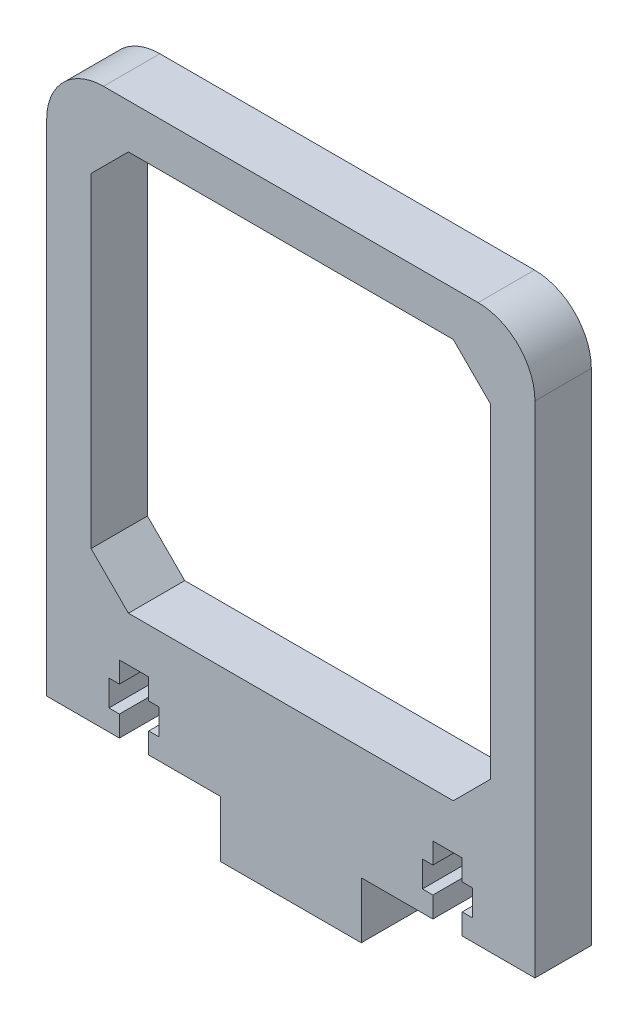
SolidWorks part; units mm, degrees
ref_plane "Front Plane" through (0, 0, 0) normal (0, 0, 1) x (1, 0, 0)
ref_plane "Top Plane" through (0, 0, 0) normal (0, 1, 0) x (1, 0, 0)
ref_plane "Right Plane" through (0, 0, 0) normal (1, 0, 0) x (0, 0, -1)
sketch "Sketch1" plane through (0, 0, 0) normal (0, 0, 1) x (1, 0, 0)
  line L0 (36.5923, 45) -> (-36.5923, 45)
  line L1 (-45, 36.5923) -> (-45, -36.5923)
  line L2 (-36.5923, -45) -> (36.5923, -45)
  line L3 (45, -36.5923) -> (45, 36.5923)
  arc A0 (45, 36.5923) -> (36.5923, 45) centre (0, 0) ccw
  arc A1 (-36.5923, 45) -> (-45, 36.5923) centre (0, 0) ccw
  arc A2 (-45, -36.5923) -> (-36.5923, -45) centre (0, 0) ccw
  arc A3 (36.5923, -45) -> (45, -36.5923) centre (0, 0) ccw
sketch "Sketch2" plane through (0, 0, 0) normal (0, 0, 1) x (1, 0, 0)
  line L0 (-55, 55) -> (-55, -70.38)
  line L1 (-55, -70.38) -> (55, -70.38)
  line L2 (55, -70.38) -> (55, 55)
  line L3 (55, 55) -> (-55, 55)
  line L4 (-45, 36.5923) -> (-45, -36.5923) construction
  line L5 (45, -36.5923) -> (45, 36.5923) construction
  line L6 (36.5923, 45) -> (-36.5923, 45) construction
  line L7 (-45, -36.5923) -> (-45, 36.5923)
  line L8 (-45, 36.5923) -> (-36.5923, 45)
  line L9 (-36.5923, 45) -> (36.5923, 45)
  line L10 (36.5923, 45) -> (45, 36.5923)
  line L11 (45, 36.5923) -> (45, -36.5923)
  line L12 (45, -36.5923) -> (36.5923, -45)
  line L13 (36.5923, -45) -> (-36.5923, -45)
  line L14 (-36.5923, -45) -> (-45, -36.5923)
  dimension "D1" = 10
  dimension "D2" = 10
  dimension "D3" = 10
  dimension "D4" = 70.38
extrude "Boss-Extrude1" add sketch "Sketch2" along normal blind 12.7
fillet "Fillet1" radius 12.8 2 edges at (-55, 55, 6.35) (55, 55, 6.35)
sketch "Sketch4" plane through (0, 0, 0) normal (0, 0, 1) x (1, 0, 0)
  line L8 (36.5923, 45) -> (-36.5923, 45)
  line L9 (-45, 36.5923) -> (-45, -36.5923)
  line L10 (-36.5923, -45) -> (36.5923, -45)
  line L11 (45, -36.5923) -> (45, 36.5923)
  arc A8 (45, 36.5923) -> (36.5923, 45) centre (0, 0) ccw
  arc A9 (-36.5923, 45) -> (-45, 36.5923) centre (0, 0) ccw
  arc A10 (-45, -36.5923) -> (-36.5923, -45) centre (0, 0) ccw
  arc A11 (36.5923, -45) -> (45, -36.5923) centre (0, 0) ccw
sketch "Sketch5" plane through (0, 0, 0) normal (0, 0, -1) x (-1, 0, 0)
  line L0 (-38.6109, -70.38) -> (-38.6109, -65.681)
  line L1 (55, -70.38) -> (-55, -70.38) construction
  line L2 (-38.6109, -65.681) -> (-40.9729, -65.681)
  line L3 (-40.9729, -65.681) -> (-40.9729, -59.839)
  line L4 (-40.9729, -59.839) -> (-38.6109, -59.839)
  line L5 (-38.6109, -59.839) -> (-38.6109, -55.14)
  line L6 (-38.6109, -55.14) -> (-32.0069, -55.14)
  line L7 (-32.0069, -55.14) -> (-32.0069, -59.839)
  line L8 (-32.0069, -59.839) -> (-29.6449, -59.839)
  line L9 (-29.6449, -59.839) -> (-29.6449, -65.681)
  line L10 (-29.6449, -65.681) -> (-32.0069, -65.681)
  line L11 (-32.0069, -65.681) -> (-32.0069, -70.38)
  line L12 (-32.0069, -70.38) -> (-38.6109, -70.38)
  line L13 (0, 49.5) -> (0, -49.5) construction
  line L14 (32.0069, -65.681) -> (32.0069, -70.38)
  line L15 (29.6449, -65.681) -> (32.0069, -65.681)
  line L16 (29.6449, -59.839) -> (29.6449, -65.681)
  line L17 (32.0069, -59.839) -> (29.6449, -59.839)
  line L18 (32.0069, -55.14) -> (32.0069, -59.839)
  line L19 (38.6109, -55.14) -> (32.0069, -55.14)
  line L20 (38.6109, -59.839) -> (38.6109, -55.14)
  line L21 (40.9729, -59.839) -> (38.6109, -59.839)
  line L22 (40.9729, -65.681) -> (40.9729, -59.839)
  line L23 (38.6109, -65.681) -> (40.9729, -65.681)
  line L24 (38.6109, -70.38) -> (38.6109, -65.681)
  line L25 (32.0069, -70.38) -> (38.6109, -70.38)
  point P28 (0, 0)
  dimension "D1" = 5.842
  dimension "D2" = 6.604
  dimension "D3" = 11.328
  dimension "D4" = 15.24
extrude "Cut-Extrude1" cut sketch "Sketch5" against normal blind 12.7
sketch "Sketch6" plane through (0, -70.38, 0) normal (0, -1, 0) x (1, 0, 0)
  line L0 (0, 0) -> (15.875, 0)
  line L1 (-32.0069, 0) -> (32.0069, 0) construction
  line L2 (15.875, 0) -> (15.875, 12.7)
  line L3 (-32.0069, 12.7) -> (32.0069, 12.7) construction
  line L4 (15.875, 12.7) -> (-15.875, 12.7)
  line L5 (-15.875, 12.7) -> (-15.875, 0)
  line L6 (-15.875, 0) -> (0, 0)
  dimension "D1" = 31.75
extrude "Boss-Extrude2" add sketch "Sketch6" along normal blind 12.7
